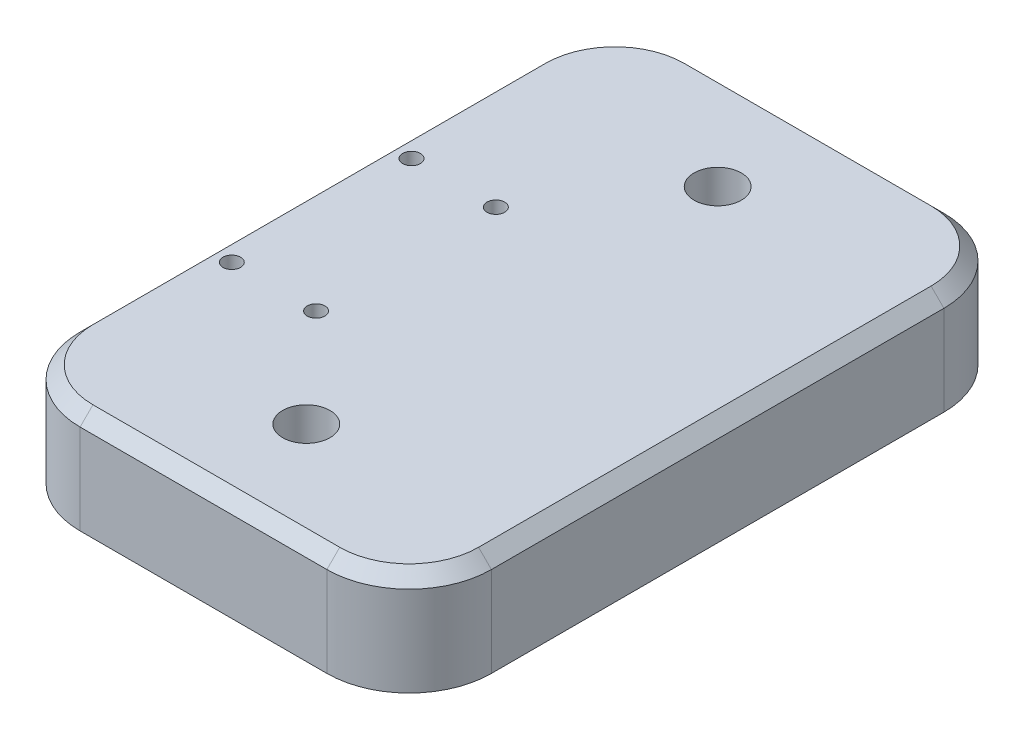
SolidWorks part; units mm, degrees
ref_plane "Front Plane" through (0, 0, 0) normal (0, 0, 1) x (1, 0, 0)
ref_plane "Top Plane" through (0, 0, 0) normal (0, 1, 0) x (1, 0, 0)
ref_plane "Right Plane" through (0, 0, 0) normal (1, 0, 0) x (0, 0, -1)
sketch "Sketch1" plane through (0, 0, 0) normal (1, 0, 0) x (0, 0, -1)
  line L3 (0, 12.7) -> (76.2, 12.7)
  line L4 (76.2, 12.7) -> (76.2, 0)
  line L5 (76.2, 0) -> (0, 0)
  line L6 (0, 12.7) -> (0, 0)
  dimension "D1" = 12.7
  dimension "D3" = 76.2
extrude "Boss-Extrude1" add sketch "Sketch1" along normal blind 50.8
sketch "Sketch3" plane through (0, 0, 0) normal (0, -1, 0) x (1, 0, 0)
  line L0 (50.8, 0) -> (0, 0) construction
  line L1 (25.4, -76.2) -> (25.4, 0) construction
  line L2 (50.8, -76.2) -> (0, -76.2) construction
  line L4 (0, -76.2) -> (0, 0) construction
  line L5 (50.8, -76.2) -> (0, -76.2) construction
  circle A1 centre (13.9065, -25.4) radius 1.0922
  circle A3 centre (25.4, -63.5) radius 2.921
  circle A4 centre (25.4, -12.7) radius 2.921
  circle A5 centre (3.4925, -25.4) radius 1.0922
  circle A6 centre (3.4925, -47.5996) radius 1.0922
  circle A7 centre (13.9065, -47.5996) radius 1.0922
  point P22 (0, 0)
  dimension "D1" = 2.1844
  dimension "D6" = 5.842
  dimension "D2" = 3.4925
  dimension "D3" = 22.1996
  dimension "D4" = 25.4
  dimension "D5" = 10.414
  dimension "D7" = 50.8
  dimension "D8" = 12.7
extrude "Cut-Extrude2" cut sketch "Sketch3" against normal through all
fillet "Fillet1" radius 10.16 4 edges at (0, 6.35, 0) (50.8, 6.35, 0) (0, 6.35, -76.2) (50.8, 6.35, -76.2)
chamfer "Chamfer1" distance 1.5875 angle 45 8 edges at (0, 12.7, -38.1) (2.9758, 12.7, -2.9758) (25.4, 12.7, 0) (47.8242, 12.7, -2.9758) (50.8, 12.7, -38.1) (47.8242, 12.7, -73.2242) (25.4, 12.7, -76.2) (2.9758, 12.7, -73.2242)
